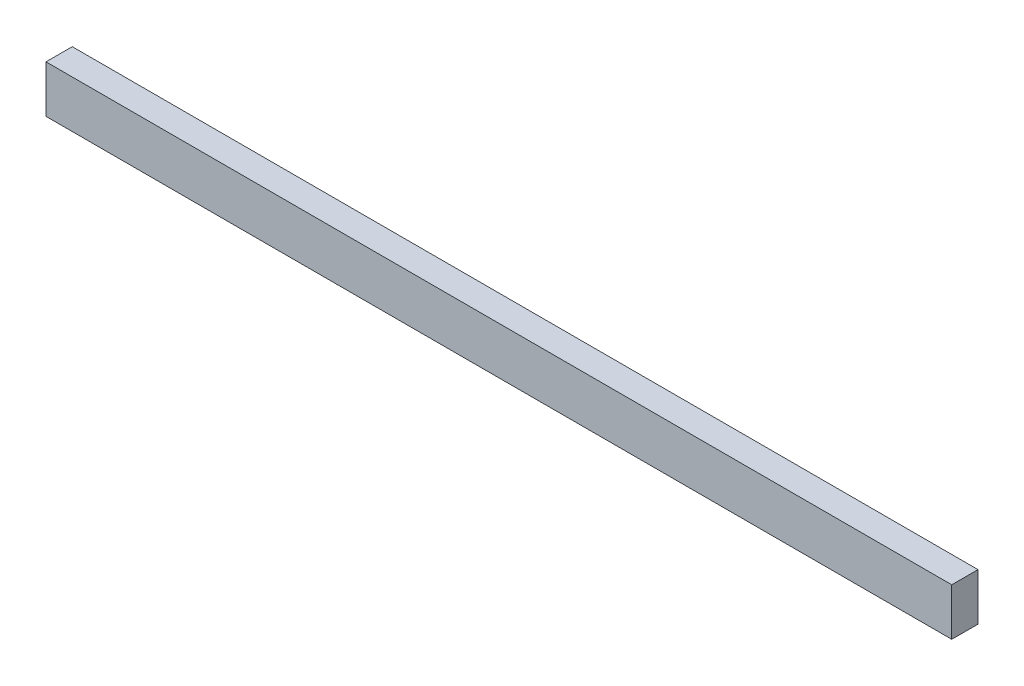
SolidWorks part; units mm, degrees
ref_plane "前视基准面" through (0, 0, 0) normal (0, 0, 1) x (1, 0, 0)
ref_plane "上视基准面" through (0, 0, 0) normal (0, 1, 0) x (1, 0, 0)
ref_plane "右视基准面" through (0, 0, 0) normal (1, 0, 0) x (0, 0, -1)
other "Configuration Table"
sketch "草图1" plane through (0, 0, 0) normal (0, 0, 1) x (1, 0, 0)
  line L0 (0, 0) -> (690, 0)
  line L1 (690, 0) -> (690, 36)
  line L2 (690, 36) -> (0, 36)
  line L3 (0, 36) -> (0, 0)
  dimension "width" = 690
  dimension "height" = 36
extrude "Crossmember" add sketch "草图1" along normal blind 20
